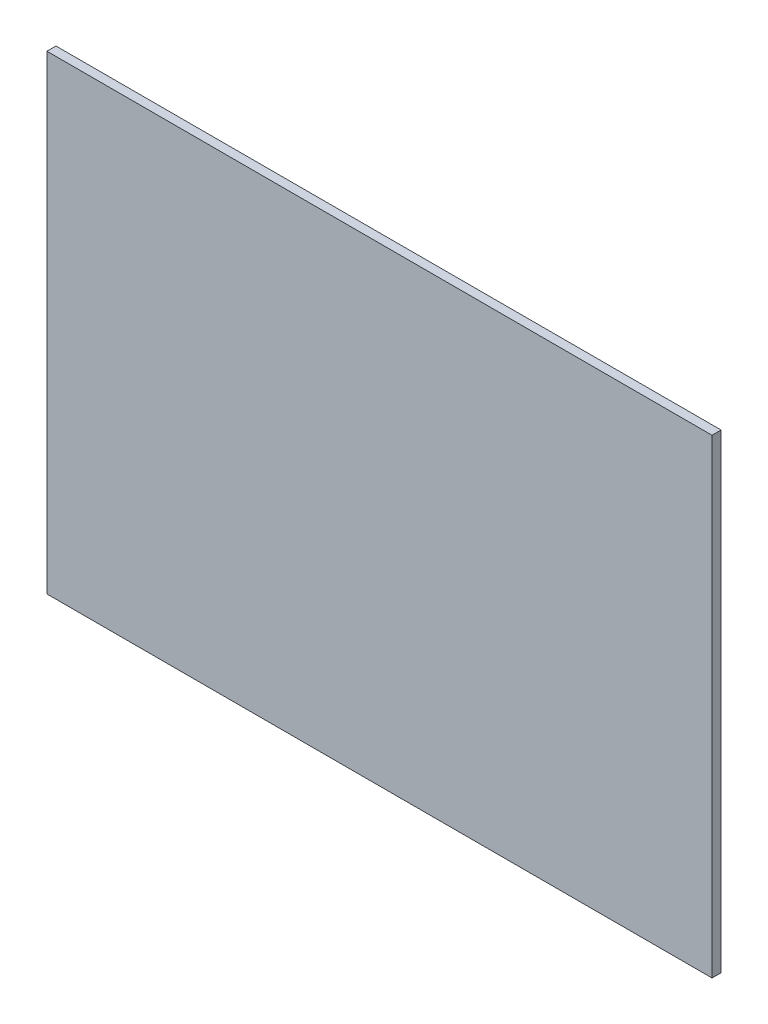
SolidWorks part; units mm, degrees
ref_plane "Front Plane" through (0, 0, 0) normal (0, 0, 1) x (1, 0, 0)
ref_plane "Top Plane" through (0, 0, 0) normal (0, 1, 0) x (1, 0, 0)
ref_plane "Right Plane" through (0, 0, 0) normal (1, 0, 0) x (0, 0, -1)
sketch "Sketch1" plane through (0, 0, 0) normal (0, 0, 1) x (1, 0, 0)
  line L1 (-36.79, -26) -> (36.79, -26)
  line L2 (-36.79, -26) -> (-36.79, 26)
  line L3 (-36.79, 26) -> (36.79, 26)
  line L4 (36.79, -26) -> (36.79, 26)
  line L5 (-36.79, -26) -> (36.79, 26) construction
  line L6 (-36.79, 26) -> (36.79, -26) construction
  point P0 (0, 0)
  dimension "D1" = 52
  dimension "D2" = 73.58
extrude "Boss-Extrude1" add sketch "Sketch1" along normal blind 1
